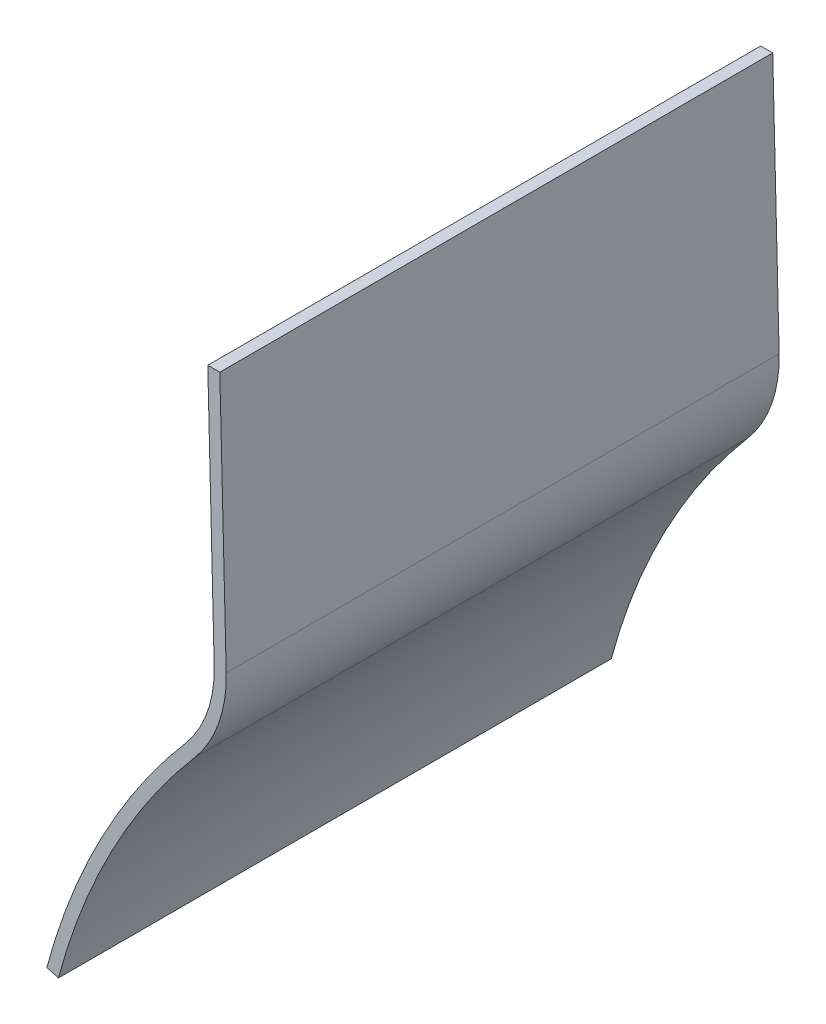
SolidWorks part; units mm, degrees
material "AISI 1020"
ref_plane "Ön Düzlem" through (0, 0, 0) normal (0, 0, 1) x (1, 0, 0)
ref_plane "Üst Düzlem" through (0, 0, 0) normal (0, 1, 0) x (1, 0, 0)
ref_plane "Sağ Düzlem" through (0, 0, 0) normal (1, 0, 0) x (0, 0, -1)
sketch "Model" plane through (0, 0, 0) normal (0, 0, 1) x (1, 0, 0)
  line L0 (2683.3612, 2448.4861) -> (2688.696, 2234.4572)
  line L1 (2673.3581, 2448.4861) -> (2678.6991, 2234.208)
  line L2 (2549.1008, 1944.8746) -> (2539.4857, 1947.6282)
  line L3 (2673.3581, 2448.4861) -> (2683.3612, 2448.4861)
  arc A0 (2662.3657, 2160.3145) -> (2688.696, 2234.4572) centre (2578.8526, 2231.7193) ccw
  arc A1 (2654.7651, 2166.8131) -> (2678.6991, 2234.208) centre (2578.8526, 2231.7193) ccw
  arc A2 (2662.3657, 2160.3145) -> (2549.1008, 1944.8746) centre (3079.9311, 1803.2909) ccw
  arc A3 (2654.7651, 2166.8131) -> (2539.4857, 1947.6282) centre (3079.9311, 1803.2909) ccw
extrude "Yükseklik-Ekstrüzyon1" add sketch "Model" along normal blind 460
